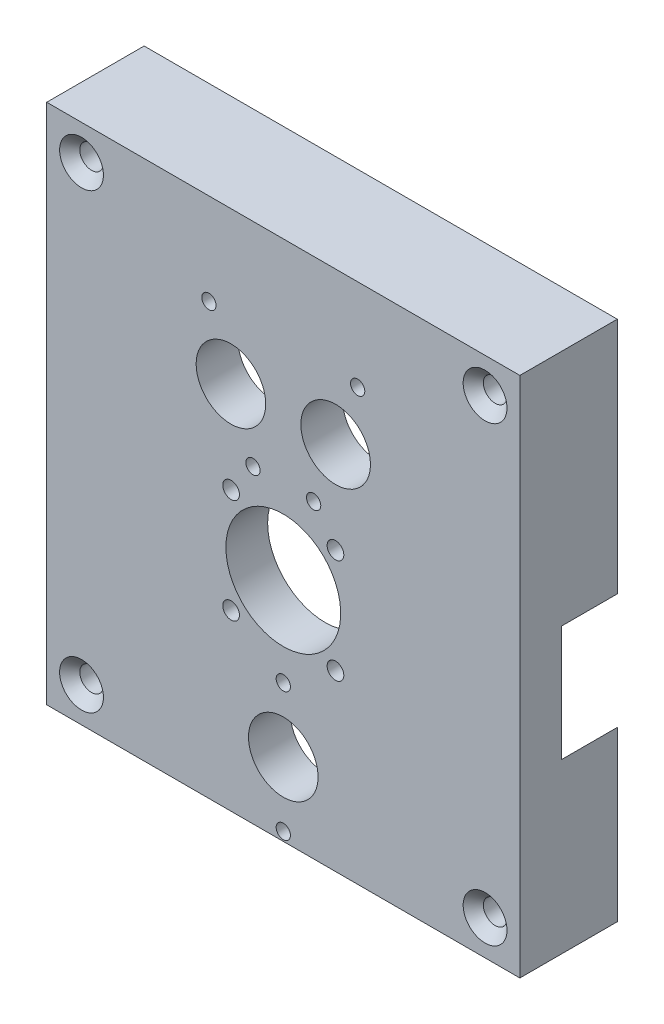
SolidWorks part; units mm, degrees
ref_plane "前基準面" through (0, 0, 0) normal (0, 0, 1) x (1, 0, 0)
ref_plane "上基準面" through (0, 0, 0) normal (0, 1, 0) x (1, 0, 0)
ref_plane "右基準面" through (0, 0, 0) normal (1, 0, 0) x (0, 0, -1)
sketch "草圖1" plane through (0, 0, 0) normal (0, 0, 1) x (1, 0, 0)
  line L1 (-34, -37.5) -> (34, -37.5)
  line L2 (-34, -37.5) -> (-34, 37.5)
  line L3 (-34, 37.5) -> (34, 37.5)
  line L4 (34, -37.5) -> (34, 37.5)
  line L5 (-34, -37.5) -> (34, 37.5) construction
  line L6 (-34, 37.5) -> (34, -37.5) construction
  point P0 (0, 0)
  dimension "D1" = 75
  dimension "D2" = 68
extrude "填料-伸長1" add sketch "草圖1" along normal blind 14
sketch "草圖2" plane through (0, 0, 0) normal (0, 0, -1) x (-1, 0, 0)
  line L0 (-34, 37.5) -> (34, 37.5) construction
  circle A0 centre (0, -5) radius 8.25
  point P2 (0, 0)
  dimension "D1" = 16.5
  dimension "D2" = 42.5
extrude "除料-伸長1" cut sketch "草圖2" against normal through all
sketch "草圖6" plane through (0, 0, 0) normal (0, 0, -1) x (-1, 0, 0)
  circle A0 centre (0, -5) radius 35
  dimension "D1" = 70
extrude "除料-伸長3" cut sketch "草圖6" against normal blind 8
hole_wizard "M2 錐坑平頭螺釘的錐孔2" positions "草圖7" profile "草圖8" countersink size "M2" standard "ISO"
sketch "草圖7" plane through (0, 0, 8) normal (0, 0, -1) x (-1, 0, 0)
  line L1 (-7.5, 2.5) -> (7.5, 2.5)
  line L2 (-7.5, 2.5) -> (-7.5, -12.5)
  line L3 (-7.5, -12.5) -> (7.5, -12.5)
  line L4 (7.5, 2.5) -> (7.5, -12.5)
  line L5 (7.5, 2.5) -> (-7.5, -12.5) construction
  line L6 (0, -5) -> (0, -13.25) construction
  circle A0 centre (0, -5) radius 8.25 construction
  point P7 (-7.5, 2.5)
  point P8 (7.5, -12.5)
  point P125 (-7.5, -12.5)
  point P126 (7.5, 2.5)
  point P151 (0, 0)
  dimension "D1" = 15
  dimension "D2" = 15
sketch "草圖8" plane through (7.5, 2.5, 8) normal (1, 0, 0) x (0, 1, 0)
  line L0 (0, 0) -> (0, 7.071)
  line L1 (0, 7.071) -> (1.2, 6.35)
  line L2 (1.2, 6.35) -> (1.2, 1)
  line L3 (1.2, 1) -> (2.2, 0)
  line L5 (2.2, 0) -> (0, 0)
  line L6 (-1.2, 1) -> (-2.2, 0) construction
  line L10 (0, 7.071) -> (-1.2, 6.35) construction
  line L11 (0, -6.35) -> (0, 107.95) construction
  dimension "鑽孔直徑" = 2.4
  dimension "鑽孔深度" = 6.35
  dimension "近端錐孔直徑" = 4.4
  dimension "近端錐孔角度" = 90
  dimension "導頭角度" = 118
sketch "草圖9" plane through (0, 0, 0) normal (0, 0, -1) x (-1, 0, 0)
  line L0 (-34, 37.5) -> (34, 37.5) construction
  line L1 (-15, -37.5) -> (15, -37.5)
  line L2 (-15, -37.5) -> (-15, 37.5)
  line L3 (-15, 37.5) -> (15, 37.5)
  line L4 (15, -37.5) -> (15, 37.5)
  line L5 (-15, -37.5) -> (15, 37.5) construction
  line L6 (-15, 37.5) -> (15, -37.5) construction
  point P0 (0, 0)
  dimension "D1" = 30
extrude "除料-伸長4" [suppressed] cut sketch "草圖9" against normal up to surface (6 mm away)
sketch "草圖10" plane through (0, 0, 14) normal (0, 0, 1) x (1, 0, 0)
  line L0 (0, -5) -> (19.0526, -16)
  line L1 (0, -5) -> (0, -27)
  line L2 (0, -5) -> (-19.0526, -16)
  circle A0 centre (0, -5) radius 22
  circle A1 centre (0, -5) radius 34.5
  circle A2 centre (0, -5) radius 9.5
  dimension "D1" = 44
  dimension "D2" = 12.5
  dimension "D3" = 12.5
  dimension "D4" = 60
  dimension "D5" = 60
hole_wizard "M2.5 螺紋孔1" positions "草圖12" profile "草圖13" tap size "M2.5" standard "ISO"
sketch "草圖12" plane through (0, 0, 8) normal (0, 0, -1) x (-1, 0, 0)
  line L0 (10.6881, 24.3654) -> (4.3608, 6.9811) construction
  line L1 (4.3608, 6.9811) -> (0, -5) construction
  line L3 (0, -5) -> (0, 26.25) construction
  circle A1 centre (0, -5) radius 31.25
  circle A2 centre (0, -5) radius 12.75
  circle A3 centre (0, -5) radius 22 construction
  point P0 (10.6881, 24.3654)
  point P2 (4.3608, 6.9811)
  dimension "D1" = 9.25
  dimension "D2" = 9.25
  dimension "D3" = 20
sketch "草圖13" plane through (-10.6881, 24.3654, 8) normal (1, 0, 0) x (0, 1, 0)
  line L0 (0, 0) -> (0, 6.9659)
  line L1 (0, 6.9659) -> (1.025, 6.35)
  line L2 (1.025, 6.35) -> (1.025, 0)
  line L5 (1.025, 0) -> (0, 0)
  line L10 (0, 6.9659) -> (-1.025, 6.35) construction
  line L11 (0, -6.35) -> (0, 107.95) construction
  dimension "螺孔鑽直徑" = 2.05
  dimension "螺孔鑽深度" = 6.35
  dimension "導頭角度" = 118
cosmetic thread "鑽孔螺紋1" parameters "D1"=5, "D2"=2.5
cosmetic thread "鑽孔螺紋2" parameters "D1"=5, "D2"=2.5
mirror "鏡射1" about plane through (0, 0, 0) normal (1, 0, 0) of "M2.5 螺紋孔1"
hole_wizard "M2.5 螺紋孔2" positions "草圖18" profile "草圖17" tap size "M2.5" standard "ISO"
sketch "草圖18" plane through (0, 0, 8) normal (0, 0, -1) x (-1, 0, 0)
  circle A0 centre (0, -5) radius 12.75
  circle A1 centre (0, -5) radius 31.25
  point P0 (0, -17.75)
  point P2 (0, -36.25)
  dimension "D1" = 18.5
sketch "草圖17" plane through (0, -17.75, 8) normal (1, 0, 0) x (0, 1, 0)
  line L0 (0, 0) -> (0, 6.9659)
  line L1 (0, 6.9659) -> (1.025, 6.35)
  line L2 (1.025, 6.35) -> (1.025, 0)
  line L5 (1.025, 0) -> (0, 0)
  line L10 (0, 6.9659) -> (-1.025, 6.35) construction
  line L11 (0, -6.35) -> (0, 107.95) construction
  dimension "螺孔鑽直徑" = 2.05
  dimension "螺孔鑽深度" = 6.35
  dimension "導頭角度" = 118
cosmetic thread "鑽孔螺紋3" parameters "D1"=5, "D2"=2.5
cosmetic thread "鑽孔螺紋4" parameters "D1"=5, "D2"=2.5
sketch "草圖19" plane through (0, 0, 8) normal (0, 0, -1) x (-1, 0, 0)
  line L0 (-10.6881, 24.3654) -> (-4.3608, 6.9811) construction
  line L1 (10.6881, 24.3654) -> (4.3608, 6.9811) construction
  line L2 (0, -17.75) -> (0, -36.25) construction
  circle A0 centre (-7.5244, 15.6732) radius 5
  circle A1 centre (7.5244, 15.6732) radius 5
  circle A2 centre (0, -27) radius 5
  dimension "D1" = 10
extrude "除料-伸長5" cut sketch "草圖19" against normal through all
hole_wizard "M3 錐坑平頭螺釘的錐孔1" positions "草圖20" profile "草圖21" countersink size "M3" standard "ISO" end condition through all
sketch "草圖20" plane through (0, 0, 14) normal (0, 0, 1) x (1, 0, 0)
  line L0 (34, 37.5) -> (-34, 37.5) construction
  line L1 (-34, 37.5) -> (-34, -37.5) construction
  line L2 (34, -37.5) -> (34, 37.5) construction
  line L3 (-34, -37.5) -> (34, -37.5) construction
  point P0 (-29, 32.5)
  point P2 (-29, -32.5)
  point P4 (29, -32.5)
  point P6 (29, 32.5)
  point P9 (0, 0)
  point P10 (0, 0)
  point P11 (0, 0)
  point P12 (0, 0)
  dimension "D1" = 5
  dimension "D2" = 5
  dimension "D3" = 5
  dimension "D4" = 5
sketch "草圖21" plane through (-29, 32.5, 14) normal (1, 0, 0) x (0, -1, 0)
  line L0 (0, 0) -> (0, 14)
  line L1 (0, 14) -> (1.7, 14)
  line L2 (1.7, 14) -> (1.7, 1.45)
  line L3 (1.7, 1.45) -> (3.15, 0)
  line L5 (3.15, 0) -> (0, 0)
  line L6 (-1.7, 1.45) -> (-3.15, 0) construction
  line L11 (0, -6.35) -> (0, 107.95) construction
  dimension "貫穿孔直徑" = 3.4
  dimension "貫穿孔深度" = 14
  dimension "近端錐孔直徑" = 6.3
  dimension "近端錐孔角度" = 90
